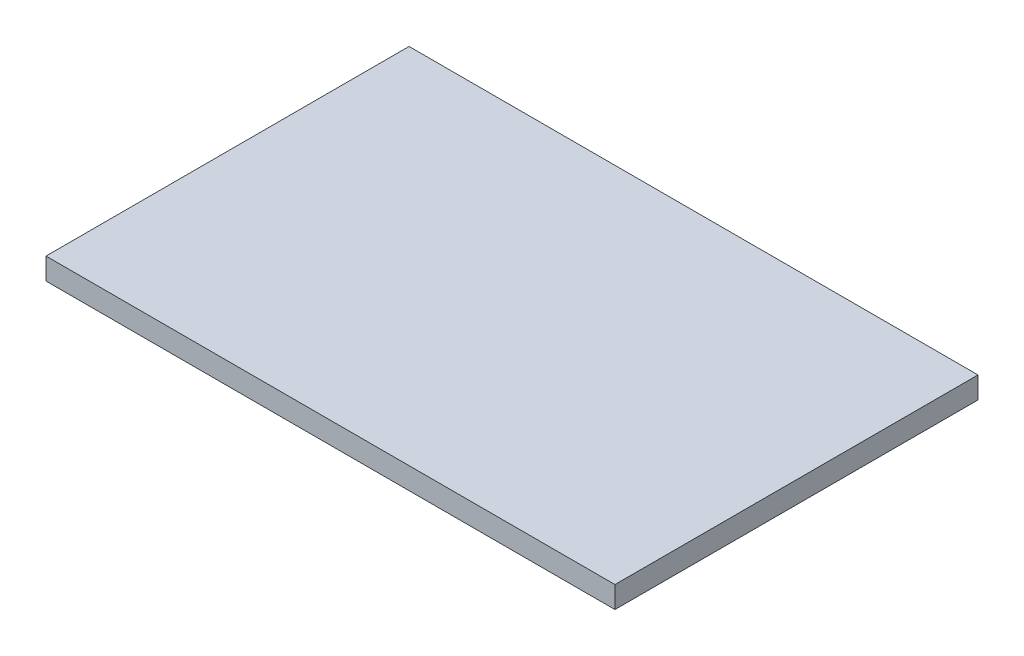
SolidWorks part; units mm, degrees
ref_plane "前视基准面" through (0, 0, 0) normal (0, 0, 1) x (1, 0, 0)
ref_plane "上视基准面" through (0, 0, 0) normal (0, 1, 0) x (1, 0, 0)
ref_plane "右视基准面" through (0, 0, 0) normal (1, 0, 0) x (0, 0, -1)
sketch "草图1" plane through (0, 0, 0) normal (0, 1, 0) x (1, 0, 0)
  line L1 (0, 0) -> (105, 0)
  line L2 (0, 0) -> (0, -67)
  line L3 (0, -67) -> (105, -67)
  line L4 (105, 0) -> (105, -67)
  dimension "D1" = 67
  dimension "D2" = 105
extrude "凸台-拉伸1" add sketch "草图1" along normal blind 4
